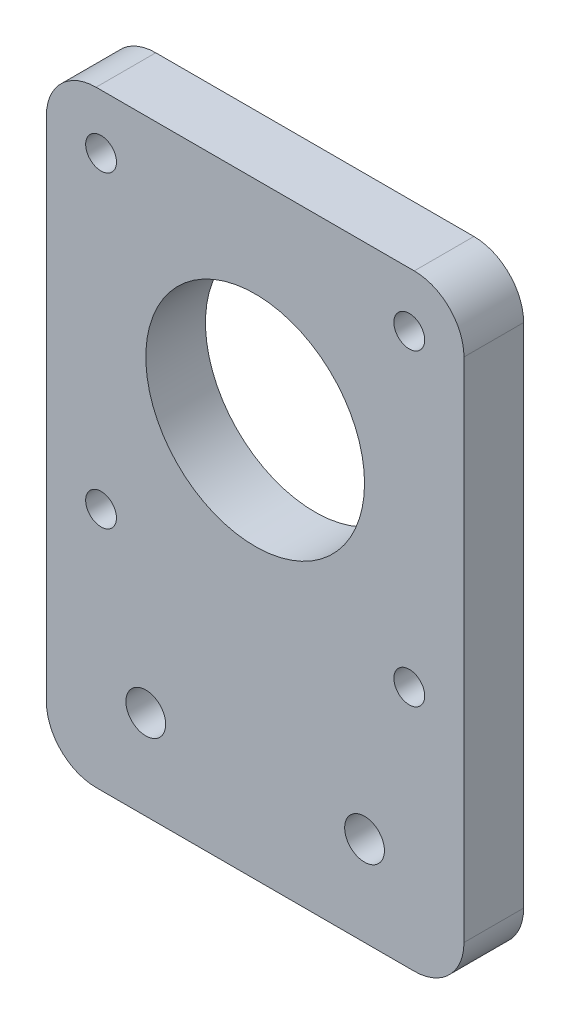
SolidWorks part; units mm, degrees
ref_plane "Front Plane" through (0, 0, 0) normal (0, 0, 1) x (1, 0, 0)
ref_plane "Top Plane" through (0, 0, 0) normal (0, 1, 0) x (1, 0, 0)
ref_plane "Right Plane" through (0, 0, 0) normal (1, 0, 0) x (0, 0, -1)
sketch "Sketch1" plane through (0, 0, 0) normal (0, 0, 1) x (1, 0, 0)
  line L1 (5, 0) -> (37, 0)
  line L2 (0, 5) -> (0, 56)
  line L3 (5, 61) -> (37, 61)
  line L4 (42, 5) -> (42, 56)
  line L5 (5.5, 24.5) -> (36.5, 24.5) construction
  line L6 (5.5, 24.5) -> (5.5, 55.5) construction
  line L7 (5.5, 55.5) -> (36.5, 55.5) construction
  line L8 (36.5, 24.5) -> (36.5, 55.5) construction
  line L9 (5.5, 24.5) -> (36.5, 55.5) construction
  line L10 (5.5, 55.5) -> (36.5, 24.5) construction
  circle A0 centre (21, 40) radius 11
  circle A1 centre (36.5, 55.5) radius 1.55
  circle A2 centre (5.5, 55.5) radius 1.55
  circle A3 centre (5.5, 24.5) radius 1.55
  circle A4 centre (36.5, 24.5) radius 1.55
  arc A5 (5, 0) -> (0, 5) centre (5, 5) cw
  arc A6 (37, 0) -> (42, 5) centre (37, 5) ccw
  arc A7 (37, 61) -> (42, 56) centre (37, 56) cw
  arc A8 (0, 56) -> (5, 61) centre (5, 56) cw
  circle A9 centre (10, 9) radius 2
  circle A10 centre (32, 9) radius 2
  point P18 (0, 0)
  point P23 (42, 61)
  point P26 (0, 61)
  dimension "D4" = 22
  dimension "D7" = 3.1
  dimension "D9" = 5
  dimension "D10" = 9
  dimension "D12" = 4
  dimension "D13" = 10
  dimension "D14" = 10
  dimension "D1" = 61
  dimension "D2" = 42
  dimension "D3" = 21
  dimension "D5" = 21
  dimension "D6" = 31
  dimension "D8" = 31
  dimension "D11" = 9
extrude "Boss-Extrude1" add sketch "Sketch1" along normal blind 6
